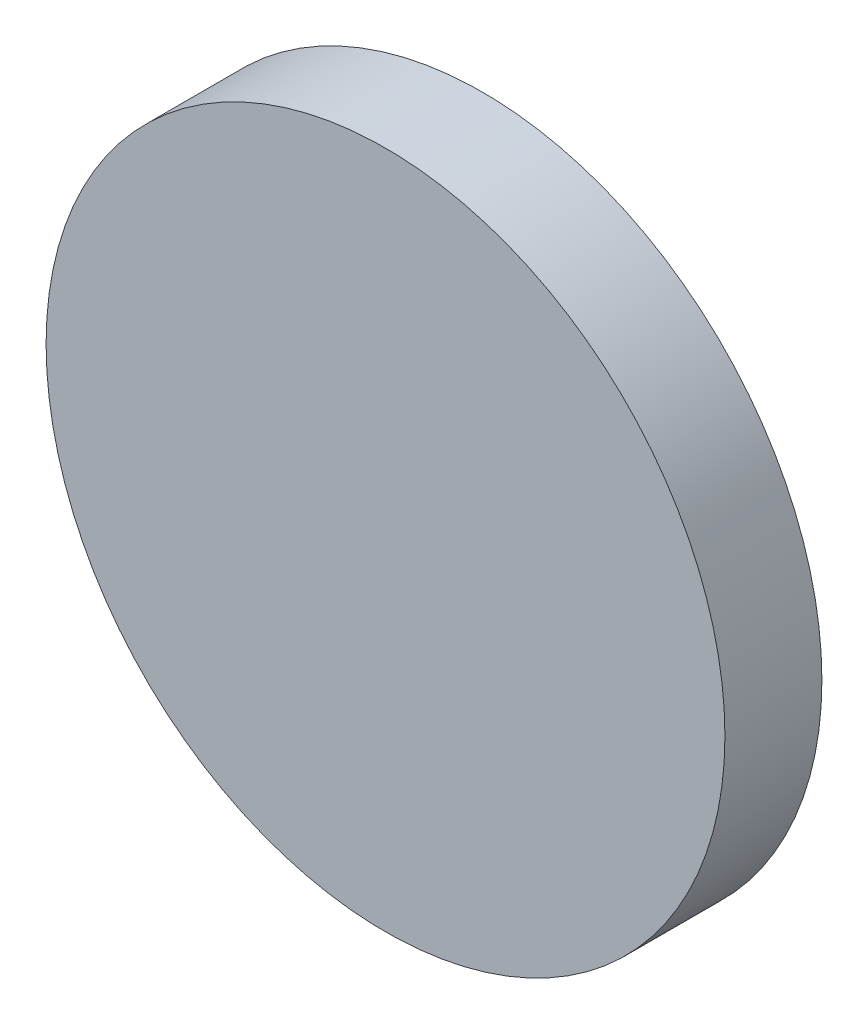
SolidWorks part; units mm, degrees
ref_plane "前视基准面" through (0, 0, 0) normal (0, 0, 1) x (1, 0, 0)
ref_plane "上视基准面" through (0, 0, 0) normal (0, 1, 0) x (1, 0, 0)
ref_plane "右视基准面" through (0, 0, 0) normal (1, 0, 0) x (0, 0, -1)
sketch "草图1" plane through (0, 0, 0) normal (0, 0, 1) x (1, 0, 0)
  circle A0 centre (0, 0) radius 70
  dimension "D1" = 140
extrude "凸台-拉伸1" add sketch "草图1" along normal blind 20
